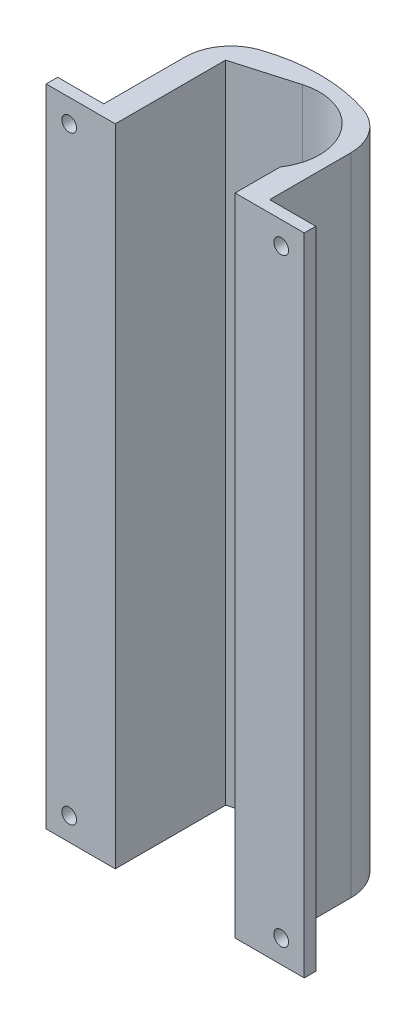
SolidWorks part; units mm, degrees
ref_plane "Front Plane" through (0, 0, 0) normal (0, 0, 1) x (1, 0, 0)
ref_plane "Top Plane" through (0, 0, 0) normal (0, 1, 0) x (1, 0, 0)
ref_plane "Right Plane" through (0, 0, 0) normal (1, 0, 0) x (0, 0, -1)
sketch "Sketch1" plane through (0, 0, 0) normal (0, 1, 0) x (1, 0, 0)
  line L0 (-20.574, -9.6521) -> (-4.162, -14.3967) construction
  line L1 (-4.1621, 14.3967) -> (-20.574, 9.652) construction
  line L2 (-20.574, 9.652) -> (-20.574, -9.6521) construction
  line L3 (-39.624, 20.7467) -> (-20.574, 20.7467) construction
  line L4 (-39.624, 20.7467) -> (-39.624, 17.5717) construction
  line L6 (12.446, 20.7467) -> (31.496, 20.7467) construction
  line L7 (-39.624, 17.5717) -> (-26.924, 17.5717) construction
  line L9 (-26.924, 17.5717) -> (-26.924, -12.8271) construction
  line L10 (31.496, 20.7467) -> (31.496, 17.5717) construction
  line L11 (31.496, 17.5717) -> (18.796, 17.5717) construction
  line L12 (18.796, 17.5717) -> (18.796, -12.8271) construction
  line L13 (-20.574, 9.652) -> (-20.574, 20.7467) construction
  line L14 (12.446, 20.7467) -> (12.446, 8.3478) construction
  line L15 (-69.4628, -37.4601) -> (67.1627, -37.4601) construction
  line L16 (-4.1621, -89.3169) -> (-20.574, -84.5722) construction
  line L17 (12.446, -95.6669) -> (12.446, -83.268)
  line L18 (-20.574, -84.5722) -> (-20.574, -95.6669)
  line L19 (18.796, -92.4919) -> (18.796, -62.0931)
  line L20 (31.496, -92.4919) -> (18.796, -92.4919)
  line L21 (31.496, -95.6669) -> (31.496, -92.4919)
  line L22 (-26.924, -92.4919) -> (-26.924, -62.0931)
  line L23 (-39.624, -92.4919) -> (-26.924, -92.4919)
  line L24 (12.446, -95.6669) -> (31.496, -95.6669)
  line L25 (-39.624, -95.6669) -> (-39.624, -92.4919)
  line L26 (-39.624, -95.6669) -> (-20.574, -95.6669)
  line L27 (-20.574, -84.5722) -> (-20.574, -65.2681)
  line L28 (-20.574, -65.2681) -> (-4.162, -60.5234)
  arc A0 (-4.162, -14.3967) -> (12.446, 8.3478) centre (0, 0) ccw construction
  arc A1 (-26.924, -12.8271) -> (18.796, -12.8271) centre (-4.064, 25.294) ccw construction
  arc A2 (12.446, 8.3478) -> (-4.1621, 14.3967) centre (0, 0) ccw construction
  arc A3 (12.446, -83.268) -> (-4.1621, -89.3169) centre (0, -74.9202) cw construction
  arc A4 (-26.924, -62.0931) -> (18.796, -62.0931) centre (-4.064, -100.2142) cw
  arc A5 (-4.162, -60.5234) -> (12.446, -83.268) centre (0, -74.9202) cw
  point P6 (12.446, 14.5473)
  dimension "D2" = 14.9863
  dimension "D14" = 37.4601
  dimension "D10" = 44.45
  dimension "D1" = 19.3041
  dimension "D3" = 16.4119
  dimension "D4" = 106.124
  dimension "D5" = 20.574
  dimension "D6" = 106.125
  dimension "D7" = 6.35
  dimension "D8" = 6.35
  dimension "D9" = 3.175
  dimension "D11" = 12.7
  dimension "D12" = 3.175
  dimension "D13" = 33.02
  dimension "D15" = 6.35
extrude "Boss-Extrude1" add sketch "Sketch1" along normal blind 177.8
fillet "Fillet2" radius 12.7 2 edges at (18.796, 88.9, 62.0931) (-26.924, 88.9, 62.0931)
sketch "Sketch2" plane through (0, 0, 92.4919) normal (0, 0, -1) x (-1, 0, 0)
  line L0 (-31.496, 0) -> (-18.796, 0) construction
  line L2 (39.624, 177.8) -> (39.624, 0) construction
  line L3 (-31.496, 177.8) -> (-18.796, 177.8) construction
  circle A0 centre (-25.146, 171.45) radius 2.032
  circle A1 centre (-25.146, 6.35) radius 2.032
  circle A2 centre (33.274, 171.45) radius 2.032
  circle A3 centre (33.274, 6.35) radius 2.032
  dimension "D1" = 4.064
  dimension "D2" = 6.35
  dimension "D3" = 6.35
  dimension "D4" = 6.35
  dimension "D5" = 6.35
extrude "Cut-Extrude1" cut sketch "Sketch2" against normal through all
